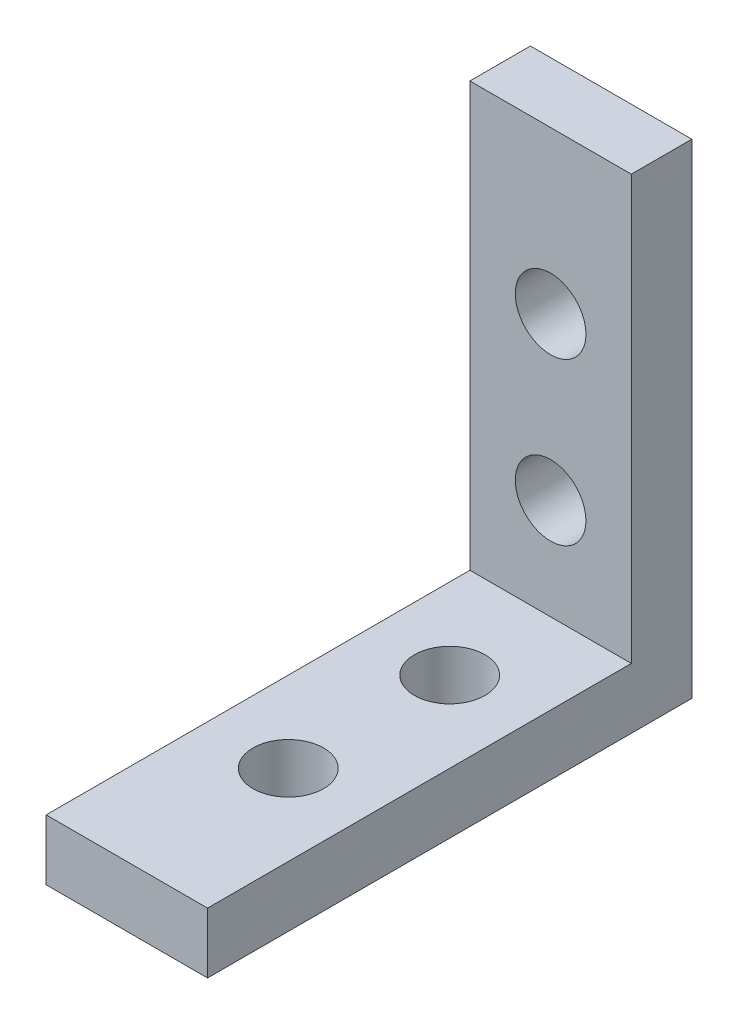
SolidWorks part; units mm, degrees
ref_plane "Front Plane" through (0, 0, 0) normal (0, 0, 1) x (1, 0, 0)
ref_plane "Top Plane" through (0, 0, 0) normal (0, 1, 0) x (1, 0, 0)
ref_plane "Right Plane" through (0, 0, 0) normal (1, 0, 0) x (0, 0, -1)
sketch "Sketch2" plane through (0, 0, 0) normal (0, 0, 1) x (1, 0, 0)
  line L1 (-57.565, 28.2942) -> (-49.565, 28.2942)
  line L2 (-57.565, 28.2942) -> (-57.565, 4.2942)
  line L3 (-57.565, 4.2942) -> (-49.565, 4.2942)
  line L4 (-49.565, 28.2942) -> (-49.565, 4.2942)
extrude "Boss-Extrude1" add sketch "Sketch2" along normal blind 3
sketch "Sketch3" plane through (0, 0, 3) normal (0, 0, 1) x (1, 0, 0)
  line L1 (-57.565, 4.2942) -> (-49.565, 4.2942)
  line L2 (-57.565, 4.2942) -> (-57.565, 7.2942)
  line L3 (-57.565, 7.2942) -> (-49.565, 7.2942)
  line L4 (-49.565, 4.2942) -> (-49.565, 7.2942)
extrude "Boss-Extrude2" add sketch "Sketch3" along normal blind 21
sketch "Sketch7" plane through (0, 0, 0) normal (0, 0, -1) x (-1, 0, 0)
  line L0 (53.565, 4.2942) -> (53.565, 28.2942) construction
  line L1 (57.565, 4.2942) -> (49.565, 4.2942) construction
  line L2 (49.565, 28.2942) -> (57.565, 28.2942) construction
  line L3 (53.565, 4.2942) -> (53.565, 12.2942) construction
  line L4 (53.565, 12.2942) -> (53.565, 20.2942) construction
  circle A0 centre (53.565, 12.2942) radius 1.75
  circle A1 centre (53.565, 20.2942) radius 1.75
extrude "Cut-Extrude3" cut sketch "Sketch7" against normal blind 10
sketch "Sketch8" plane through (0, 4.2942, 0) normal (0, -1, 0) x (1, 0, 0)
  line L0 (-53.565, 0) -> (-53.565, 24) construction
  line L1 (-57.565, 0) -> (-49.565, 0) construction
  line L2 (-57.565, 24) -> (-49.565, 24) construction
  line L3 (-53.565, 0) -> (-53.565, 8) construction
  line L4 (-53.565, 8) -> (-53.565, 16) construction
  circle A0 centre (-53.565, 8) radius 1.75
  circle A1 centre (-53.565, 16) radius 1.75
extrude "Cut-Extrude4" cut sketch "Sketch8" against normal blind 10
